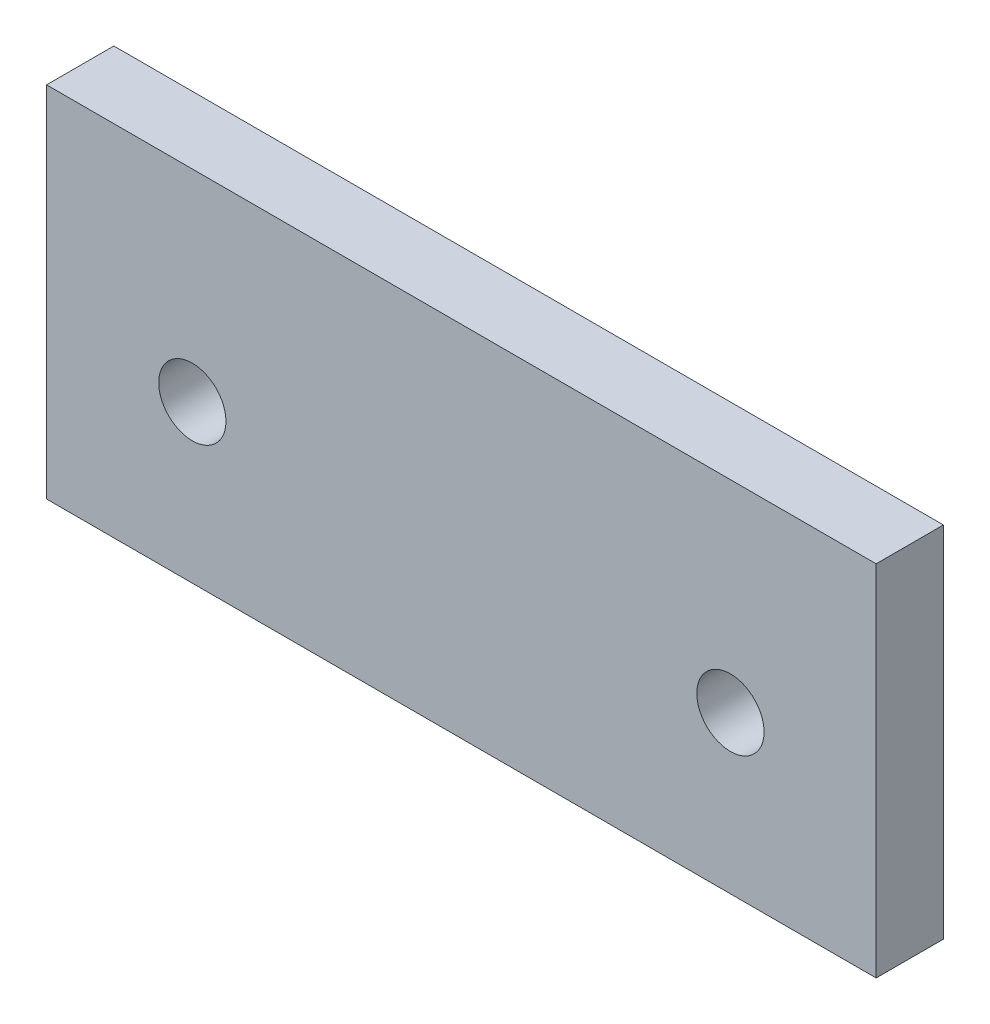
SolidWorks part; units mm, degrees
ref_plane "Front Plane" through (0, 0, 0) normal (0, 0, 1) x (1, 0, 0)
ref_plane "Top Plane" through (0, 0, 0) normal (0, 1, 0) x (1, 0, 0)
ref_plane "Right Plane" through (0, 0, 0) normal (1, 0, 0) x (0, 0, -1)
sketch "Sketch1" plane through (0, 0, 0) normal (0, 0, 1) x (1, 0, 0)
  line L1 (0, 0) -> (-74, 0)
  line L2 (0, 0) -> (0, 32)
  line L3 (0, 32) -> (-74, 32)
  line L4 (-74, 0) -> (-74, 32)
  line L5 (0, 0) -> (-74, 32) construction
  line L6 (0, 32) -> (-74, 0) construction
  point P4 (-37, 16)
  dimension "D1" = 74
  dimension "D2" = 32
extrude "Boss-Extrude1" add sketch "Sketch1" along normal blind 6
sketch "Sketch2" plane through (0, 0, 6) normal (0, 0, 1) x (1, 0, 0)
  line L0 (0, 0) -> (0, 32) construction
  line L1 (0, 32) -> (-74, 32) construction
  line L2 (-74, 32) -> (-74, 0) construction
  circle A0 centre (-13, 14) radius 3
  circle A1 centre (-61, 14) radius 3
  dimension "D3" = 6
  dimension "D6" = 6
  dimension "D1" = 13
  dimension "D2" = 18
  dimension "D4" = 18
  dimension "D5" = 13
extrude "Cut-Extrude1" cut sketch "Sketch2" against normal blind 6
